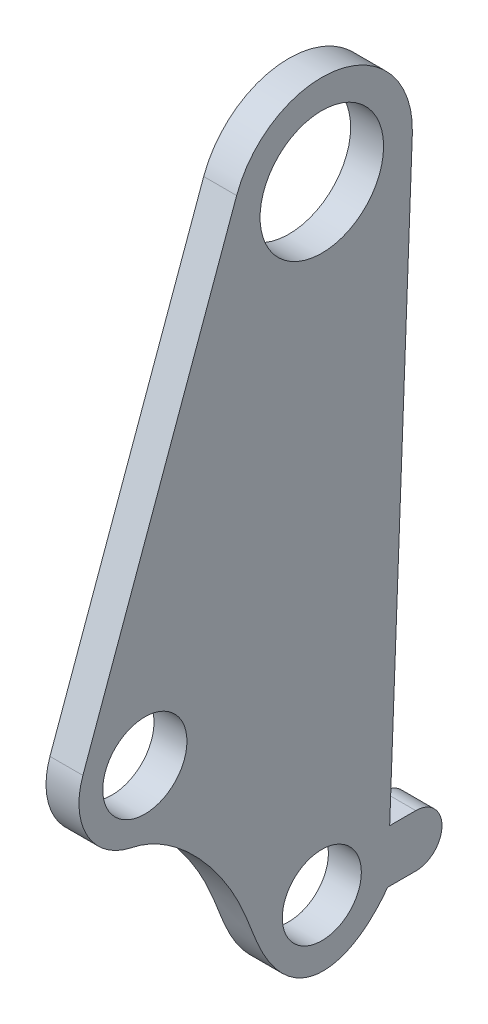
SolidWorks part; units mm, degrees
ref_plane "Front Plane" through (0, 0, 0) normal (0, 0, 1) x (1, 0, 0)
ref_plane "Top Plane" through (0, 0, 0) normal (0, 1, 0) x (1, 0, 0)
ref_plane "Right Plane" through (0, 0, 0) normal (1, 0, 0) x (0, 0, -1)
sketch "Sketch1" plane through (0, 0, 0) normal (1, 0, 0) x (0, 0, -1)
  line L0 (0, 0) -> (0, -47.625) construction
  line L1 (0, 0) -> (-13.6463, -32.1486) construction
  line L2 (-6.569, 2.3745) -> (-18.4238, -30.4217)
  line L5 (6.9798, -0.2691) -> (5.2319, -45.6057)
  line L6 (5.2319, -45.6057) -> (7.2445, -45.6057)
  line L7 (5.0762, -49.6443) -> (7.2445, -49.6443)
  circle A0 centre (0, 0) radius 4.7625
  circle A1 centre (-13.6463, -32.1486) radius 3.2461
  circle A2 centre (0, -47.625) radius 3.048
  arc A3 (-6.569, 2.3745) -> (6.9798, -0.2691) centre (0, 0) cw
  arc A4 (-14.6696, -37.1245) -> (-18.4238, -30.4217) centre (-13.6463, -32.1486) cw
  arc A7 (7.2445, -45.6057) -> (7.2445, -49.6443) centre (7.2445, -47.625) cw
  spline S0 degree 3 poles (-14.6696, -37.1245) (-11.3157, -37.8143) (-6.9209, -42.7155) (-3.1495, -54.1754) (2.0166, -53.8016) (5.0762, -49.6443) knots 0 0 0 0 0.321173 0.421173 1 1 1 1
  dimension "D1" = 47.625
  dimension "D2" = 34.925
  dimension "D3" = 9.525
  dimension "D4" = 23
  dimension "D6" = 4.0386
  dimension "D7" = 6.985
  dimension "D9" = 6.096
  dimension "D5" = 6.4922
  dimension "D8" = 5.08
extrude "Boss-Extrude1" add sketch "Sketch1" along normal blind 2.54
